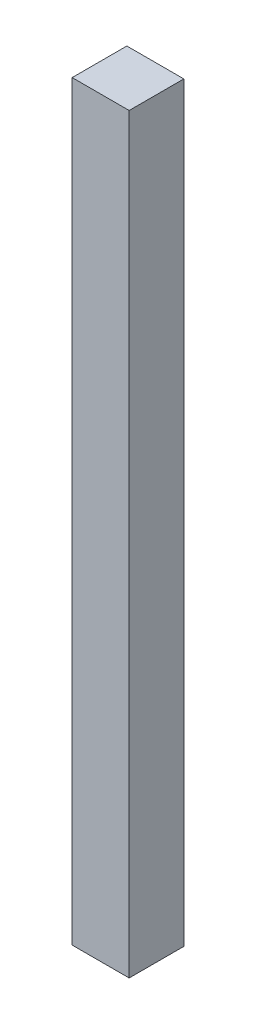
SolidWorks part; units mm, degrees
ref_plane "Front" through (0, 0, 0) normal (0, 0, 1) x (1, 0, 0)
ref_plane "Top" through (0, 0, 0) normal (0, 1, 0) x (1, 0, 0)
ref_plane "Right" through (0, 0, 0) normal (1, 0, 0) x (0, 0, -1)
sketch "Sketch1" plane through (0, 0, 0) normal (0, 1, 0) x (1, 0, 0)
  line L1 (0, 0) -> (16.376, 0)
  line L2 (0, 0) -> (0, 15.7157)
  line L3 (0, 15.7157) -> (16.376, 15.7157)
  line L4 (16.376, 0) -> (16.376, 15.7157)
extrude "Boss-Extrude1" add sketch "Sketch1" along normal blind 215.9
